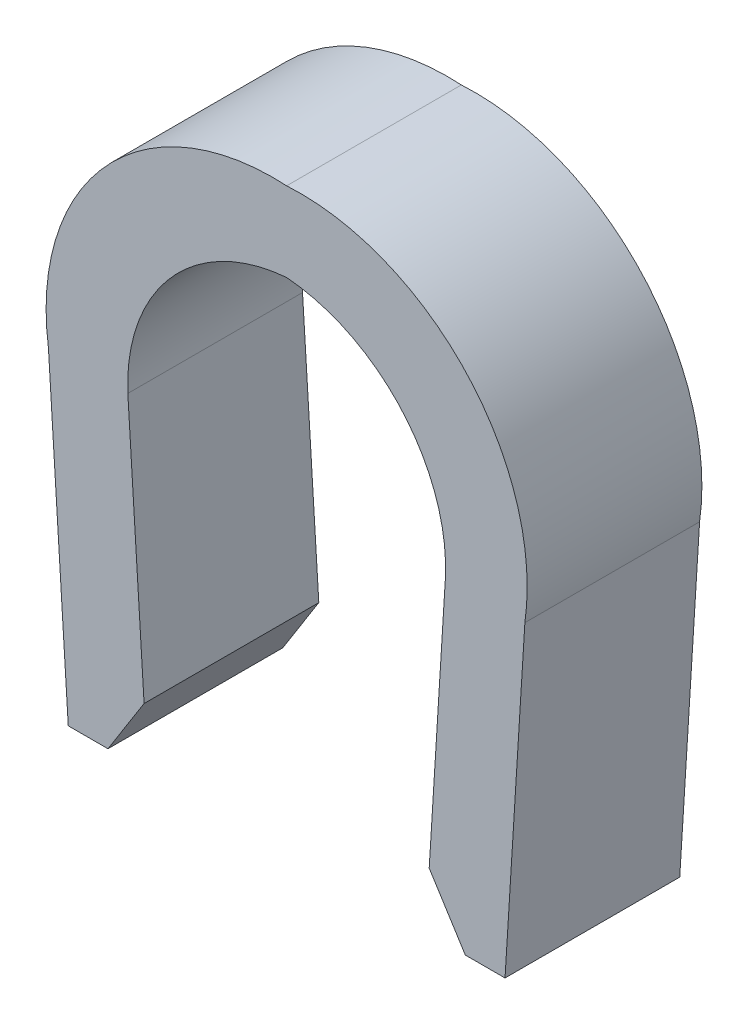
SolidWorks part; units mm, degrees
ref_plane "Front Plane" through (0, 0, 0) normal (0, 0, 1) x (1, 0, 0)
ref_plane "Top Plane" through (0, 0, 0) normal (0, 1, 0) x (1, 0, 0)
ref_plane "Right Plane" through (0, 0, 0) normal (1, 0, 0) x (0, 0, -1)
sketch "Sketch1" plane through (0, 0, 0) normal (0, 0, 1) x (1, 0, 0)
  line L0 (-4, 3.7693) -> (-3.5, -4.2307)
  line L5 (-3.5, -4.2307) -> (-5.5, -4.2307)
  line L6 (-5.5, -4.2307) -> (-6, 3.7693)
  line L10 (0, 7.8443) -> (0, -6.8113) construction
  line L11 (5.5, -4.2307) -> (6, 3.7693)
  line L12 (3.5, -4.2307) -> (5.5, -4.2307)
  line L13 (4, 3.7693) -> (3.5, -4.2307)
  arc A4 (-4, 3.7693) -> (0, 8.2978) centre (0.3521, 3.9559) cw
  arc A5 (-6, 3.7693) -> (0, 10.2978) centre (-0.3314, 4.581) cw
  arc A6 (6, 3.7693) -> (0, 10.2978) centre (0.3314, 4.581) ccw
  arc A7 (4, 3.7693) -> (0, 8.2978) centre (-0.3521, 3.9559) ccw
  point P6 (0, 10.0671)
  dimension "D1" = 8
  dimension "D2" = 4
  dimension "D3" = 2
  dimension "D4" = 2
  dimension "D5" = 4.5285
  dimension "D6" = 3.5
extrude "Boss-Extrude1" add sketch "Sketch1" along normal blind 4.4
sketch "Sketch2" plane through (0, 0, 0) normal (0, 0, 1) x (1, 0, 0)
  line L0 (-3.5, -4.2307) -> (-4.5, -4.2307)
  line L1 (-5.5, -4.2307) -> (-3.5, -4.2307) construction
  line L2 (-4.5, -4.2307) -> (-3.5901, -2.7891)
  line L3 (-3.5, -4.2307) -> (-4, 3.7693) construction
  line L4 (-3.5901, -2.7891) -> (-3.5, -4.2307)
  line L5 (3.5, -4.2307) -> (3.5901, -2.7891)
  line L6 (4, 3.7693) -> (3.5, -4.2307) construction
  line L7 (3.5901, -2.7891) -> (4.5, -4.2307)
  line L8 (3.5, -4.2307) -> (5.5, -4.2307) construction
  line L9 (4.5, -4.2307) -> (3.5, -4.2307)
  point P16 (-4.5, -4.2307)
extrude "Cut-Extrude2" cut sketch "Sketch2" along normal through all both and the other way through all
equation "\"thiccness\"=3.9"
equation "\"D1@Boss-Extrude1\"=\"thiccness\""
